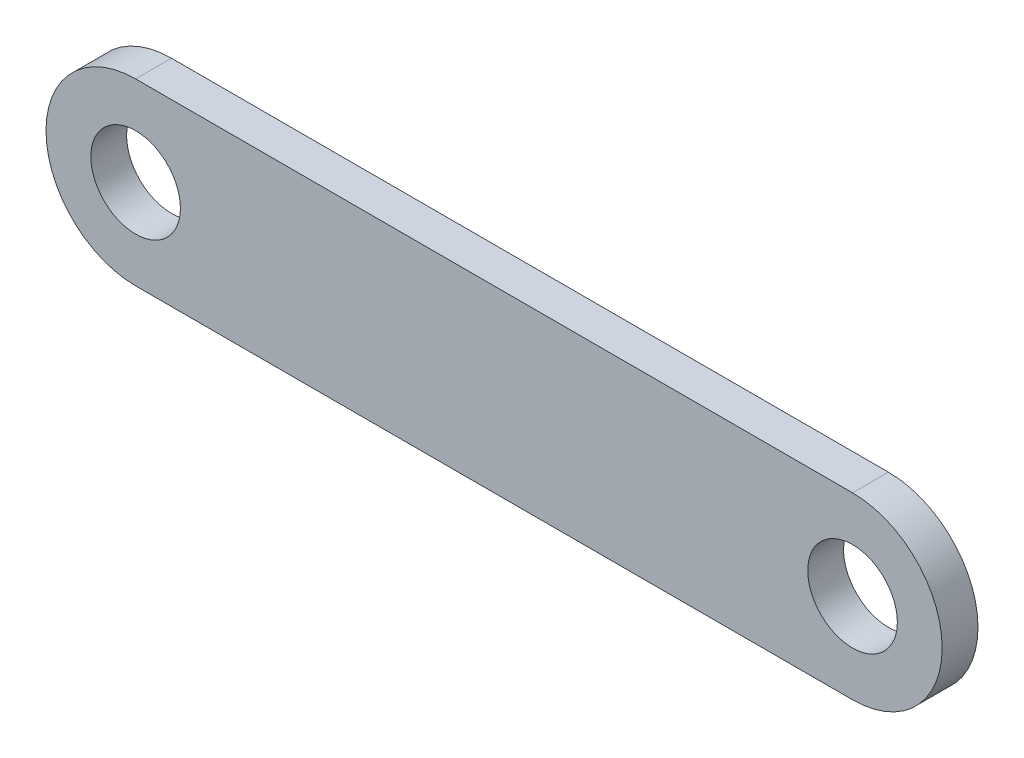
SolidWorks part; units mm, degrees
ref_plane "Plan 1" through (0, 0, 0) normal (0, 0, 1) x (1, 0, 0)
ref_plane "Plan 2" through (0, 0, 0) normal (0, 1, 0) x (1, 0, 0)
ref_plane "Plan 3" through (0, 0, 0) normal (1, 0, 0) x (0, 0, -1)
sketch "Esquisse1" plane through (0, 0, 0) normal (0, 0, 1) x (1, 0, 0)
  line L0 (0, 0) -> (80, 0) construction
  line L1 (0, 10) -> (80, 10)
  line L2 (80, -10) -> (0, -10)
  circle A0 centre (0, 0) radius 5
  circle A1 centre (80, 0) radius 5
  arc A2 (80, 10) -> (80, -10) centre (80, 0) cw
  arc A3 (0, 10) -> (0, -10) centre (0, 0) ccw
  dimension "D1" = 10
  dimension "D2" = 10
  dimension "D3" = 80
extrude "Base-Extrusion" add sketch "Esquisse1" along normal mid plane 4
sketch "Esquisse2" plane through (0, 0, 0) normal (0, 0, 1) x (1, 0, 0)
  point P0 (0, 0)
sketch "Esquisse3" plane through (0, 0, 0) normal (0, 0, 1) x (1, 0, 0)
  point P0 (0, 0)
